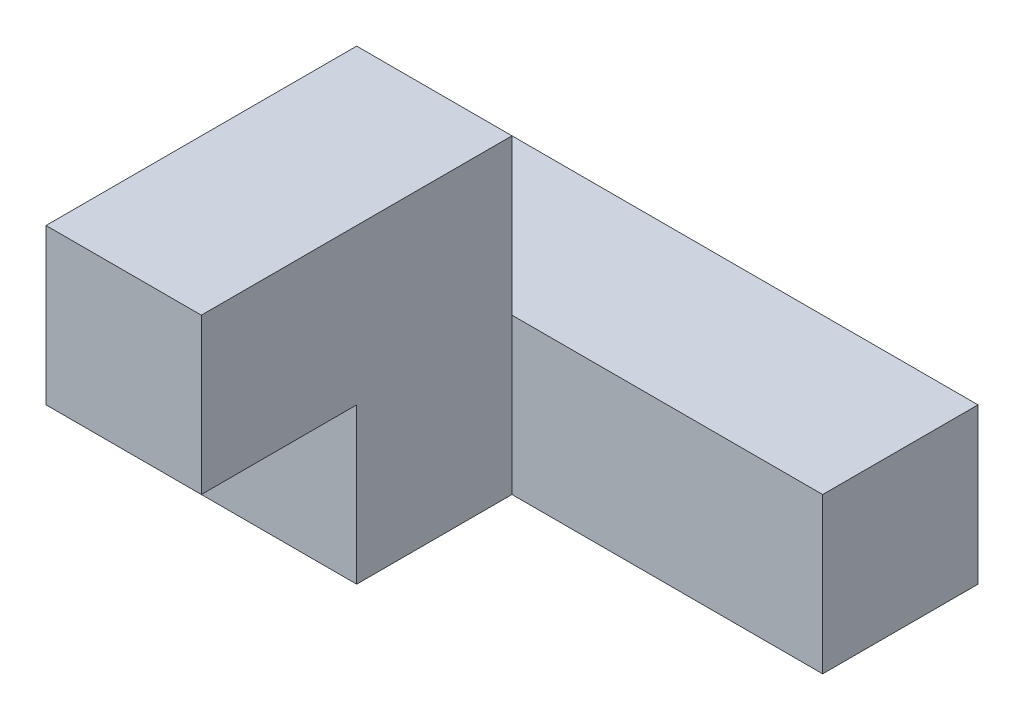
SolidWorks part; units mm, degrees
ref_plane "Front Plane" through (0, 0, 0) normal (0, 0, 1) x (1, 0, 0)
ref_plane "Top Plane" through (0, 0, 0) normal (0, 1, 0) x (1, 0, 0)
ref_plane "Right Plane" through (0, 0, 0) normal (1, 0, 0) x (0, 0, -1)
sketch "Sketch1" plane through (0, 0, 0) normal (0, 1, 0) x (1, 0, 0)
  line L1 (0, 0) -> (25.4, 0)
  line L2 (0, 0) -> (0, 50.8)
  line L3 (0, 50.8) -> (25.4, 50.8)
  line L4 (25.4, 0) -> (25.4, 50.8)
  dimension "D1" = 25.4
  dimension "D2" = 50.8
extrude "Boss-Extrude1" add sketch "Sketch1" along normal blind 25.4
sketch "Sketch2" plane through (25.4, 0, 0) normal (1, 0, 0) x (0, 0, -1)
  line L0 (0, 25.4) -> (50.8, 25.4) construction
  line L1 (25.4, 25.4) -> (50.8, 25.4)
  line L2 (25.4, 25.4) -> (25.4, 0)
  line L3 (25.4, 0) -> (50.8, 0)
  line L4 (50.8, 25.4) -> (50.8, 0)
extrude "Boss-Extrude2" add sketch "Sketch2" along normal blind 50.8
sketch "Sketch3" plane through (0, 25.4, 0) normal (0, 1, 0) x (1, 0, 0)
  line L1 (25.4, 25.4) -> (0, 25.4)
  line L2 (25.4, 25.4) -> (25.4, 0)
  line L3 (25.4, 0) -> (0, 0)
  line L4 (0, 25.4) -> (0, 0)
extrude "Boss-Extrude3" add sketch "Sketch3" along normal blind 25.4
sketch "Sketch4" plane through (0, 0, 0) normal (0, 0, 1) x (1, 0, 0)
  line L0 (25.4, 50.8) -> (25.4, 0) construction
  line L1 (0, 50.8) -> (25.4, 50.8)
  line L2 (0, 50.8) -> (0, 25.4)
  line L3 (0, 25.4) -> (25.4, 25.4)
  line L4 (25.4, 50.8) -> (25.4, 25.4)
extrude "Boss-Extrude4" add sketch "Sketch4" along normal blind 25.4
